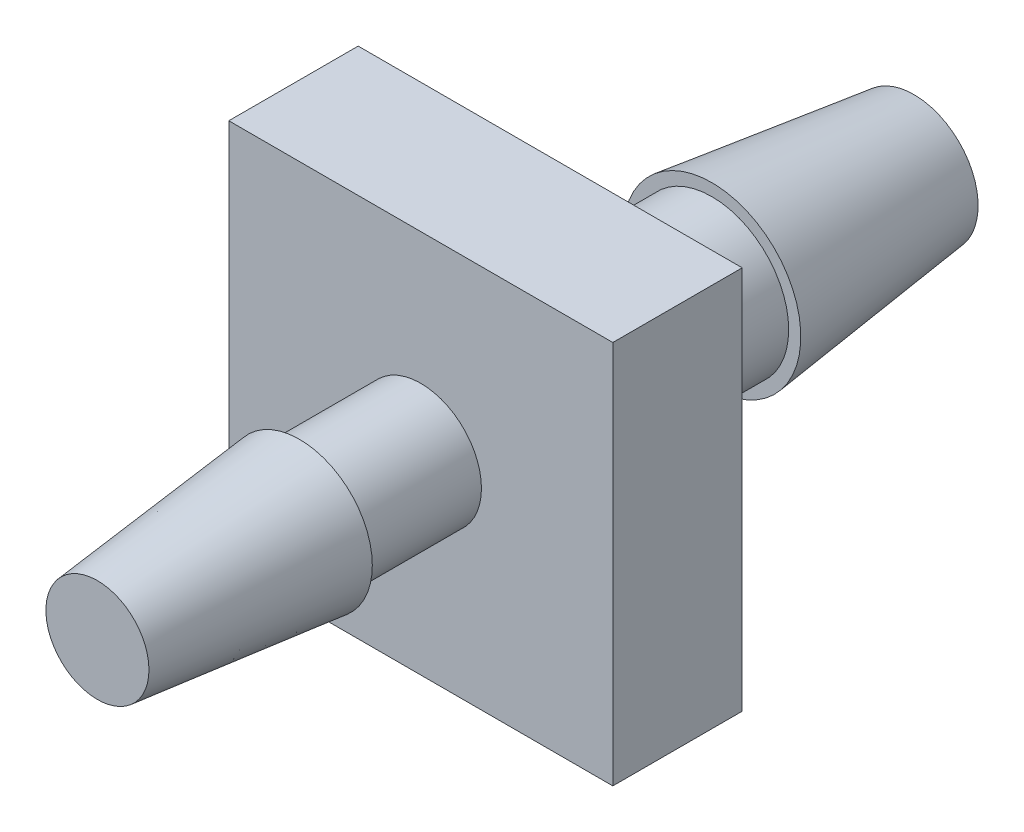
SolidWorks part; units mm, degrees
material "ABS"
ref_plane "Plan de face" through (0, 0, 0) normal (0, 0, 1) x (1, 0, 0)
ref_plane "Plan de dessus" through (0, 0, 0) normal (0, 1, 0) x (1, 0, 0)
ref_plane "Plan de droite" through (0, 0, 0) normal (1, 0, 0) x (0, 0, -1)
sketch "Esquisse1" plane through (0, 0, 0) normal (0, 0, 1) x (1, 0, 0)
  line L1 (-7.2076, 1.4734) -> (2.2924, 1.4734)
  line L2 (-7.2076, 1.4734) -> (-7.2076, -8.0266)
  line L3 (-7.2076, -8.0266) -> (2.2924, -8.0266)
  line L4 (2.2924, 1.4734) -> (2.2924, -8.0266)
  dimension "D1" = 9.5
  dimension "D2" = 9.5
extrude "Extrusion1" add sketch "Esquisse1" along normal blind 3.2
sketch "Esquisse2" plane through (0, 0, 3.2) normal (0, 0, 1) x (1, 0, 0)
  circle A0 centre (-2.4576, -3.2766) radius 1.5
  dimension "D1" = 3
extrude "Extrusion2" add sketch "Esquisse2" along normal blind 3
sketch "Esquisse3" plane through (0, 0, 6.2) normal (0, 0, 1) x (1, 0, 0)
  circle A0 centre (-2.4576, -3.2766) radius 1.8
  dimension "D1" = 3.6
extrude "Extrusion3" add sketch "Esquisse3" along normal blind 5 draft 6
sketch "Esquisse4" plane through (0, 0, 0) normal (0, 0, -1) x (-1, 0, 0)
  circle A0 centre (2.4576, -3.2766) radius 1.9
  dimension "D1" = 3.8
extrude "Extrusion4" add sketch "Esquisse4" along normal blind 4
sketch "Esquisse5" plane through (0, 0, -4) normal (0, 0, -1) x (-1, 0, 0)
  circle A0 centre (2.4576, -3.2766) radius 2.2
extrude "Extrusion5" add sketch "Esquisse5" along normal blind 5 draft 7
